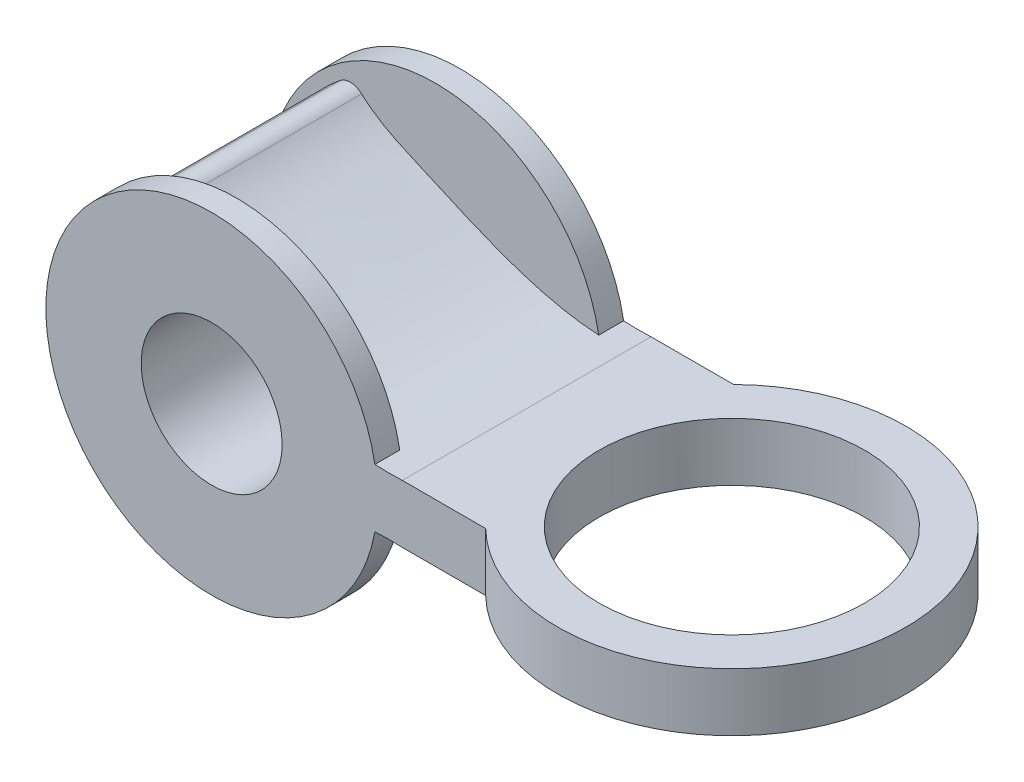
SolidWorks part; units mm, degrees
ref_plane "Front Plane" through (0, 0, 0) normal (0, 0, 1) x (1, 0, 0)
ref_plane "Top Plane" through (0, 0, 0) normal (0, 1, 0) x (1, 0, 0)
ref_plane "Right Plane" through (0, 0, 0) normal (1, 0, 0) x (0, 0, -1)
sketch "Sketch1" plane through (0, 0, 0) normal (0, 0, 1) x (1, 0, 0)
  circle A0 centre (0, 0) radius 20
  dimension "D1" = 40
extrude "Boss-Extrude1" add sketch "Sketch1" against normal blind 3
sketch "Sketch2" plane through (0, 0, 0) normal (0, 0, 1) x (1, 0, 0)
  line L0 (-20, 0) -> (37.0234, 0) construction
  line L2 (22.9952, 3.5) -> (35.373, 3.5)
  line L4 (22.9952, -3.5) -> (35.373, -3.5)
  line L5 (35.373, 3.5) -> (35.373, -3.5)
  line L6 (-35.373, 3.5) -> (35.373, -3.5) construction
  line L7 (-35.373, -3.5) -> (35.373, 3.5) construction
  circle A0 centre (0, 0) radius 20 construction
  arc A1 (-10.0123, 15.596) -> (-10.0123, -15.596) centre (0, 0) ccw
  spline S0 degree 3 poles (-10.0123, 15.596) (-7.8201, 12.9046) (3.1886, 8.3141) (13.8332, 3.0526) (22.9952, 3.5) knots 0 0 0 0 0.276488 1 1 1 1
  spline S1 degree 3 poles (-10.0123, -15.596) (-7.8201, -12.9046) (3.1886, -8.3141) (13.8332, -3.0526) (22.9952, -3.5) knots 0 0 0 0 0.276488 1 1 1 1
  point P6 (0, 0)
  point P15 (6.3814, 7.1241)
  point P17 (-0.6601, 9.7647)
  point P19 (22.9952, 3.5)
  point P21 (5.3362, 7.2341)
  point P22 (-1.3203, 10.0948)
  point P23 (-10.0123, 15.596)
  point P24 (0, 0)
  point P25 (-1.7604, 10.3148)
  dimension "D1" = 7
extrude "Boss-Extrude2" add sketch "Sketch2" against normal blind 30
fillet "Fillet1" radius 2 2 edges at (-10.0123, 15.596, -16.5) (-10.0123, -15.596, -16.5)
sketch "Sketch3" plane through (0, -3.5, 0) normal (0, -1, 0) x (1, 0, 0)
  circle A0 centre (47.6998, -15.0457) radius 21
  dimension "D1" = 42
extrude "Boss-Extrude3" add sketch "Sketch3" against normal blind 7
sketch "Sketch4" plane through (0, 0, -30) normal (0, 0, -1) x (-1, 0, 0)
  circle A0 centre (0, 0) radius 20
  dimension "D1" = 40
extrude "Boss-Extrude4" add sketch "Sketch4" against normal blind 3
sketch "Sketch5" plane through (0, 0, 0) normal (0, 0, 1) x (1, 0, 0)
  circle A0 centre (0, 0) radius 8.5
  dimension "D1" = 17
extrude "Cut-Extrude1" cut sketch "Sketch5" against normal blind 43
sketch "Sketch6" plane through (0, -3.5, 0) normal (0, -1, 0) x (1, 0, 0)
  circle A0 centre (47.6998, -15.0457) radius 16
  dimension "D1" = 32
extrude "Cut-Extrude2" cut sketch "Sketch6" against normal blind 43
